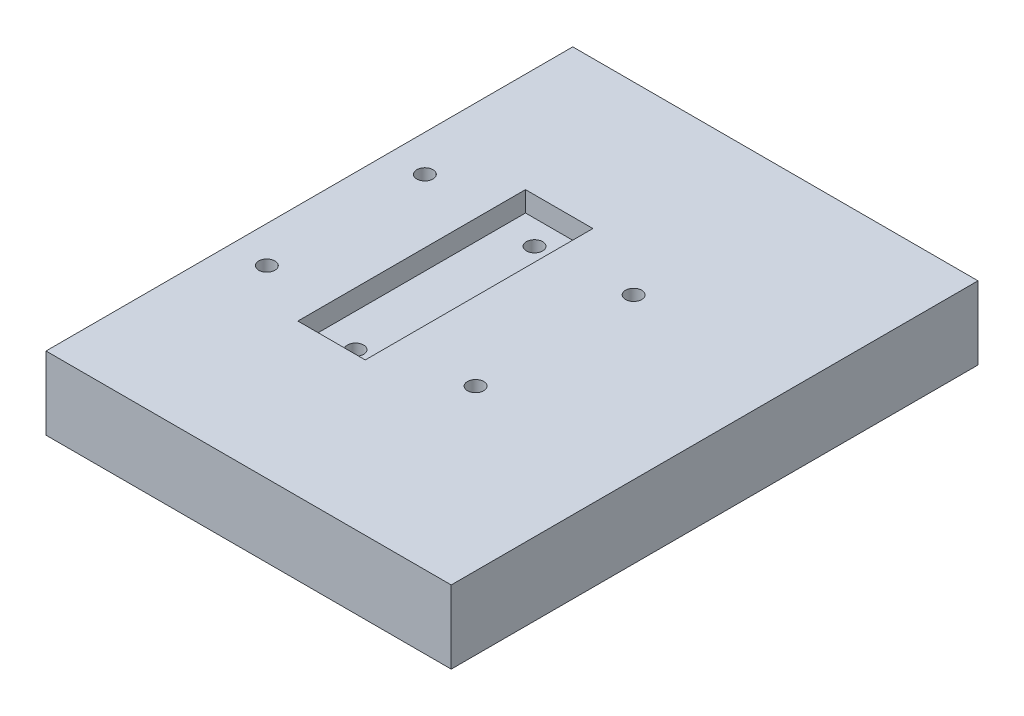
SolidWorks part; units mm, degrees
ref_plane "Plan de face" through (0, 0, 0) normal (0, 0, 1) x (1, 0, 0)
ref_plane "Plan de dessus" through (0, 0, 0) normal (0, 1, 0) x (1, 0, 0)
ref_plane "Plan de droite" through (0, 0, 0) normal (1, 0, 0) x (0, 0, -1)
sketch "Esquisse1" plane through (0, 0, 0) normal (0, 1, 0) x (1, 0, 0)
  line L0 (-72.4825, -71.858) -> (-49.4825, -71.858) construction
  line L1 (-149.4825, -6.858) -> (-49.4825, -6.858)
  line L2 (-149.4825, -6.858) -> (-149.4825, -136.858)
  line L3 (-149.4825, -136.858) -> (-49.4825, -136.858)
  line L4 (-49.4825, -6.858) -> (-49.4825, -136.858)
  line L5 (-72.4825, -75.858) -> (-72.4825, -67.858) construction
  dimension "D1" = 100
  dimension "D2" = 130
extrude "Boss.-Extru.1" add sketch "Esquisse1" along normal blind 18
sketch "Esquisse2" plane through (0, 18, 0) normal (0, 1, 0) x (1, 0, 0)
  line L0 (-118.5734, -93.3787) -> (-114.5734, -93.3787) construction
  line L1 (-118.5734, -92.8787) -> (-118.5734, -93.8787) construction
  line L2 (-114.5734, -93.8787) -> (-114.5734, -92.8787) construction
  circle A0 centre (-116.5734, -93.3787) radius 2
  circle A1 centre (-116.5734, -49.2029) radius 2 construction
extrude "Enlèv. mat.-Extru.1" cut sketch "Esquisse2" against normal through all
sketch "Esquisse3" plane through (0, 0, 0) normal (0, -1, 0) x (1, 0, 0)
  line L0 (-88.9663, 44.358) -> (-88.9663, 99.358) construction
  line L1 (-79.9663, 44.358) -> (-97.9663, 44.358) construction
  line L2 (-79.9663, 99.358) -> (-97.9663, 99.358) construction
  line L3 (-140.4825, 44.358) -> (-140.4825, 99.358) construction
  line L4 (-131.4825, 44.358) -> (-149.4825, 44.358) construction
  line L5 (-131.4825, 99.358) -> (-149.4825, 99.358) construction
  circle A0 centre (-88.9663, 52.358) radius 2
  circle A1 centre (-88.9663, 91.358) radius 2
  circle A2 centre (-140.4825, 91.358) radius 2
  circle A3 centre (-140.4825, 52.358) radius 2
  dimension "D1" = 4
  dimension "D2" = 8
  dimension "D3" = 8
  dimension "D4" = 8
  dimension "D5" = 8
extrude "Enlèv. mat.-Extru.2" cut sketch "Esquisse3" against normal through all
sketch "Esquisse6" plane through (0, 18, 0) normal (0, 1, 0) x (1, 0, 0)
  line L0 (-116.5734, -93.3787) -> (-116.5734, -49.2029) construction
  line L1 (-108.1716, -99.3787) -> (-124.804, -99.3787)
  line L2 (-108.1716, -99.3787) -> (-108.1716, -43.2029)
  line L3 (-108.1716, -43.2029) -> (-124.804, -43.2029)
  line L4 (-124.804, -99.3787) -> (-124.804, -43.2029)
  line L5 (-116.5734, -49.2029) -> (-116.4878, -43.2029) construction
  line L6 (-116.5734, -93.3787) -> (-116.4878, -99.3787) construction
  dimension "D1" = 6
  dimension "D2" = 6
extrude "Enlèv. mat.-Extru.5" cut sketch "Esquisse6" against normal blind 5
sketch "Esquisse4" plane through (0, 18, 0) normal (0, 1, 0) x (1, 0, 0)
  circle A0 centre (-116.5734, -49.2029) radius 2
sketch "Esquisse8" plane through (0, 13, 0) normal (0, 1, 0) x (1, 0, 0)
  circle A0 centre (-116.5734, -49.2029) radius 2
extrude "Enlèv. mat.-Extru.6" cut sketch "Esquisse8" against normal blind 3
